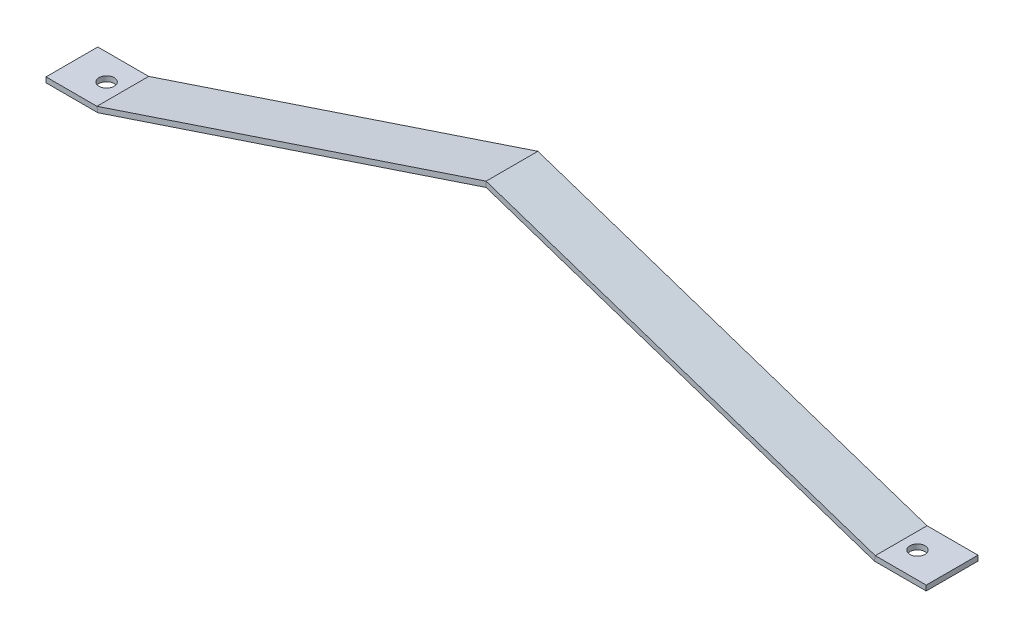
SolidWorks part; units mm, degrees
ref_plane "Front Plane" through (0, 0, 0) normal (0, 0, 1) x (1, 0, 0)
ref_plane "Top Plane" through (0, 0, 0) normal (0, 1, 0) x (1, 0, 0)
ref_plane "Right Plane" through (0, 0, 0) normal (1, 0, 0) x (0, 0, -1)
sketch "Sketch1" plane through (0, 0, 0) normal (0, 0, 1) x (1, 0, 0)
  line L0 (-40.64, 0) -> (-21.59, 6.35)
  line L1 (-21.59, 6.35) -> (-2.54, 0)
  line L2 (-40.64, 0) -> (-43.18, 0)
  line L3 (-2.54, 0) -> (0, 0)
  dimension "D1" = 43.18
  dimension "D2" = 19.05
  dimension "D3" = 19.05
  dimension "D4" = 6.35
  dimension "D5" = 0
  dimension "D6" = 2.54
  dimension "D7" = 2.54
sketch "Sketch7" plane through (0, 0, 0) normal (1, 0, 0) x (0, 0, -1)
  line L1 (0, 0) -> (2.54, 0)
  line L2 (0, 0) -> (0, 0.254)
  line L3 (0, 0.254) -> (2.54, 0.254)
  line L4 (2.54, 0) -> (2.54, 0.254)
  dimension "D1" = 0.254
  dimension "D2" = 2.54
sweep "Sweep2" add profiles "Sketch7" path "Sketch1"
hole_wizard "#69 (0.0292) Diameter Hole1" positions "Sketch6" profile "Sketch5" hole size "#69" standard "ANSI Inch" end condition through all
sketch "Sketch6" plane through (0, 0, 0) normal (0, 1, 0) x (1, 0, 0)
  line L4 (-40.6812, 0) -> (-43.18, 0) construction
  line L5 (-2.4988, 0) -> (0, 0) construction
  line L6 (0, 2.54) -> (0, 0) construction
  point P11 (-41.4782, 1.27)
  point P13 (-1.7018, 1.27)
  point P26 (-1.2494, 0)
  dimension "D1" = 39.7764
  dimension "D2" = 1.27
  dimension "D3" = 1.27
  dimension "D4" = 1.7018
sketch "Sketch5" plane through (-41.4782, 0, -1.27) normal (1, 0, 0) x (0, 0, -1)
  line L0 (0, 0) -> (0, 6.6177)
  line L1 (0, 6.6177) -> (0.3708, 6.6177)
  line L2 (0.3708, 6.6177) -> (0.3708, 0)
  line L5 (0.3708, 0) -> (0, 0)
  line L11 (0, -6.35) -> (0, 107.95) construction
  dimension "Thru Hole Dia." = 0.7417
  dimension "Thru Hole Depth" = 6.6177
